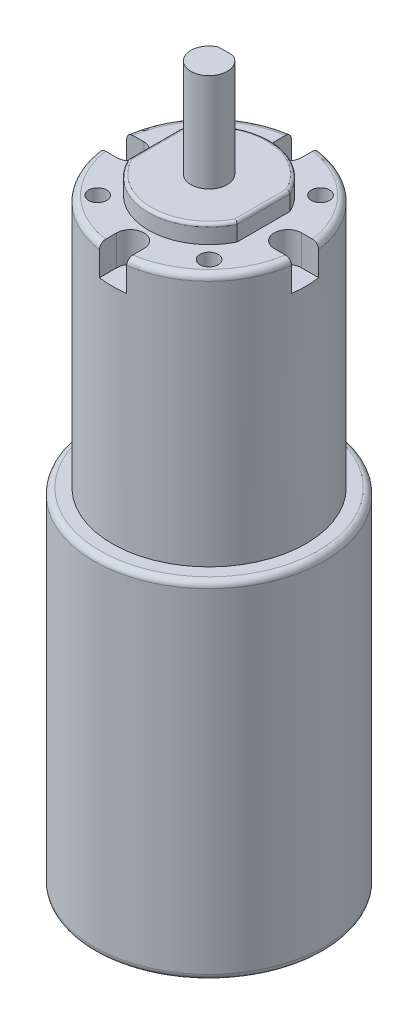
SolidWorks part; units mm, degrees
ref_plane "Front Plane" through (0, 0, 0) normal (0, 0, 1) x (1, 0, 0)
ref_plane "Top Plane" through (0, 0, 0) normal (0, 1, 0) x (1, 0, 0)
ref_plane "Right Plane" through (0, 0, 0) normal (1, 0, 0) x (0, 0, -1)
sketch "Sketch3" plane through (0, 0, 0) normal (0, 1, 0) x (1, 0, 0)
  circle A0 centre (0, 0) radius 3
  dimension "D1" = 6
extrude "Boss-Extrude2" add sketch "Sketch3" along normal blind 16.2
ref_plane "Plane1" through (0, 16.2, 0) normal (0, 1, 0) x (1, 0, 0)
sketch "Sketch4" plane through (0, 16.2, 0) normal (0, 1, 0) x (1, 0, 0)
  line L1 (-1.199, 2.75) -> (1.199, 2.75)
  arc A0 (1.199, 2.75) -> (-1.199, 2.75) centre (0, 0) ccw
  point P7 (0, 2.75)
extrude "Cut-Extrude1" cut sketch "Sketch4" against normal blind 12
sketch "Sketch5" plane through (0, 0, 0) normal (0, 1, 0) x (1, 0, 0)
  line L1 (-9, -4.3589) -> (-9, 4.3589)
  line L2 (9, -4.3589) -> (9, 4.3589)
  arc A0 (-9, -4.3589) -> (9, -4.3589) centre (0, 0) ccw
  arc A1 (9, 4.3589) -> (-9, 4.3589) centre (0, 0) ccw
  point P6 (0, 0)
  point P9 (-9, 0)
  point P12 (9, 0)
extrude "Boss-Extrude3" add sketch "Sketch5" against normal blind 3
ref_plane "Plane3" through (0, -3, 0) normal (0, -1, 0) x (-1, 0, 0)
sketch "Sketch7" plane through (0, -3, 0) normal (0, -1, 0) x (-1, 0, 0)
  circle A0 centre (0, 0) radius 13 construction
  circle A1 centre (0, 0) radius 16
extrude "Boss-Extrude4" add sketch "Sketch7" along normal blind 41.8 contours A1
ref_plane "Plane4" through (0, -44.8, 0) normal (0, -1, 0) x (-1, 0, 0)
sketch "Sketch8" plane through (0, -44.8, 0) normal (0, -1, 0) x (-1, 0, 0)
  circle A0 centre (0, 0) radius 19
extrude "Boss-Extrude5" add sketch "Sketch8" along normal blind 57.1
fillet "Fillet1" radius 1 2 edges at (0, -44.8, -19) (0, -3, -16)
fillet "Fillet2" radius 0.5 4 edges at (-9, 0, 0) (9, 0, 0) (0, 0, 10) (0, 0, -10)
sketch "Sketch9" plane through (0, -3, 0) normal (0, -1, 0) x (-1, 0, 0)
  line L0 (-17.5, -2.25) -> (-17.5, 2.25)
  line L1 (2.25, -17.5) -> (-2.25, -17.5)
  line L2 (2.25, -17.5) -> (2.25, -13)
  line L3 (-17.5, -2.25) -> (-13, -2.25)
  line L4 (-2.25, -17.5) -> (-2.25, -13)
  line L5 (-17.5, 2.25) -> (-13, 2.25)
  line L6 (-2.25, 17.5) -> (2.25, 17.5)
  line L7 (-2.25, 17.5) -> (-2.25, 13)
  line L8 (2.25, 17.5) -> (2.25, 13)
  line L9 (17.5, 2.25) -> (17.5, -2.25)
  line L10 (17.5, 2.25) -> (13, 2.25)
  line L11 (17.5, -2.25) -> (13, -2.25)
  arc A0 (2.2416, -12.8053) -> (-2.2416, -12.8053) centre (0, 0) ccw construction
  arc A1 (2.25, -13) -> (-2.25, -13) centre (0, -13) ccw
  arc A2 (-13, -2.25) -> (-13, 2.25) centre (-13, 0) ccw
  arc A3 (-2.25, 13) -> (2.25, 13) centre (0, 13) ccw
  arc A4 (13, 2.25) -> (13, -2.25) centre (13, 0) ccw
  circle A5 centre (9.1924, -9.1924) radius 1.5
  circle A6 centre (-9.1924, -9.1924) radius 1.5
  circle A7 centre (-9.1924, 9.1924) radius 1.5
  circle A8 centre (9.1924, 9.1924) radius 1.5
  point P5 (0, -15.25)
  point P14 (-15.25, 0)
  point P20 (0, 15.25)
  point P26 (15.25, 0)
  point P31 (0, 0)
  point P40 (0, 0)
  dimension "D1" = 4
  dimension "D2" = 4
extrude "Cut-Extrude2" cut sketch "Sketch9" along normal blind 5
fillet "Fillet3" radius 1 1 edges at (0, -101.9, -19)
